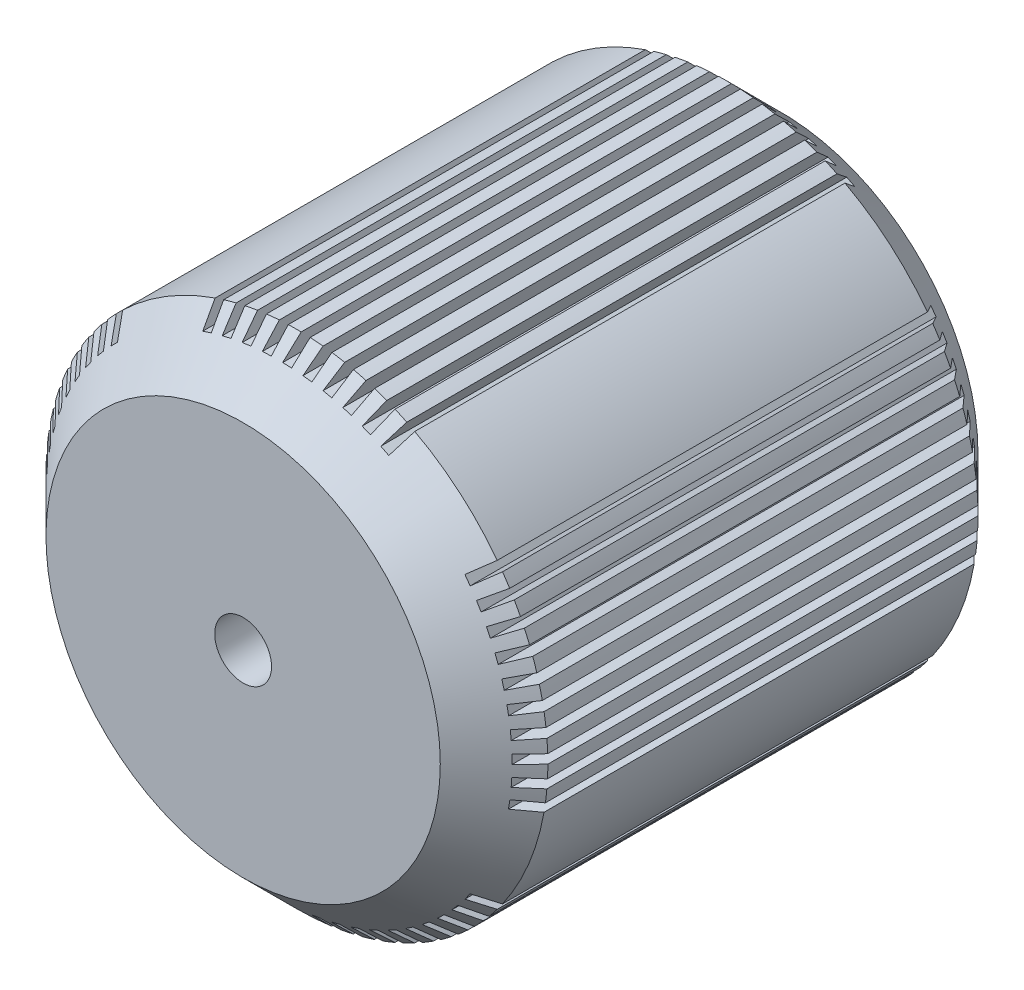
SolidWorks part; units mm, degrees
ref_plane "Plan de face" through (0, 0, 0) normal (0, 0, 1) x (1, 0, 0)
ref_plane "Plan de dessus" through (0, 0, 0) normal (0, 1, 0) x (1, 0, 0)
ref_plane "Plan de droite" through (0, 0, 0) normal (1, 0, 0) x (0, 0, -1)
sketch "Esquisse1" plane through (0, 0, 0) normal (0, 0, 1) x (1, 0, 0)
  circle A0 centre (0, 0) radius 14
  dimension "D1" = 28
extrude "Boss.-Extru.1" add sketch "Esquisse1" along normal blind 30
chamfer "Chanfrein1" distance 3 angle 45 2 edges at (14, 0, 30) (14, 0, 0)
sketch "Esquisse2" plane through (0, 0, 30) normal (0, 0, 1) x (1, 0, 0)
  circle A0 centre (0, 0) radius 1.585
  dimension "D1" = 3.17
extrude "Enlèv. mat.-Extru.1" cut sketch "Esquisse2" against normal blind 20
sketch "Esquisse3" plane through (0, 0, 30) normal (0, 0, 1) x (1, 0, 0)
  line L1 (-14, 0.25) -> (-13, 0.25)
  line L3 (-14, -0.25) -> (-13, -0.25)
  line L4 (-13, 0.25) -> (-13, -0.25)
  arc A1 (-14, -0.25) -> (-14, 0.25) centre (-10.0252, 0) cw
  dimension "D1" = 0.25
  dimension "D2" = 13
  dimension "D3" = 1
  dimension "D4" = 1
  dimension "D5" = 0.5
extrude "Enlèv. mat.-Extru.6" cut sketch "Esquisse3" against normal through all
pattern_circular "Répétition circulaire1" count 10 every 5 about axis through (0, 0, 0) along (0, 0, 1) of "Enlèv. mat.-Extru.6"
pattern_circular "Répétition circulaire2" count 5 every 72 about axis through (0, 0, 0) along (0, 0, 1) of "Répétition circulaire1", "Enlèv. mat.-Extru.6"
